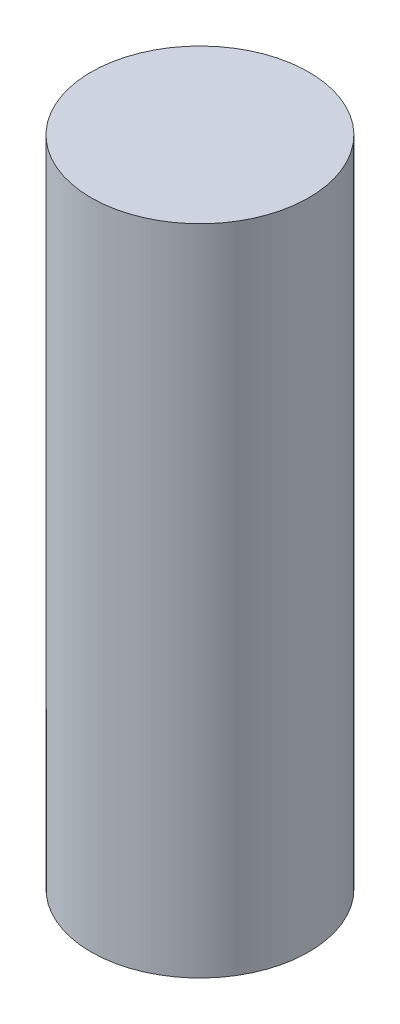
SolidWorks part; units mm, degrees
ref_plane "Front Plane" through (0, 0, 0) normal (0, 0, 1) x (1, 0, 0)
ref_plane "Top Plane" through (0, 0, 0) normal (0, 1, 0) x (1, 0, 0)
ref_plane "Right Plane" through (0, 0, 0) normal (1, 0, 0) x (0, 0, -1)
sketch "Sketch1" plane through (0, 0, 0) normal (0, 1, 0) x (1, 0, 0)
  circle A0 centre (0, 0) radius 25
  dimension "D1" = 50
extrude "Boss-Extrude1" add sketch "Sketch1" along normal blind 150
